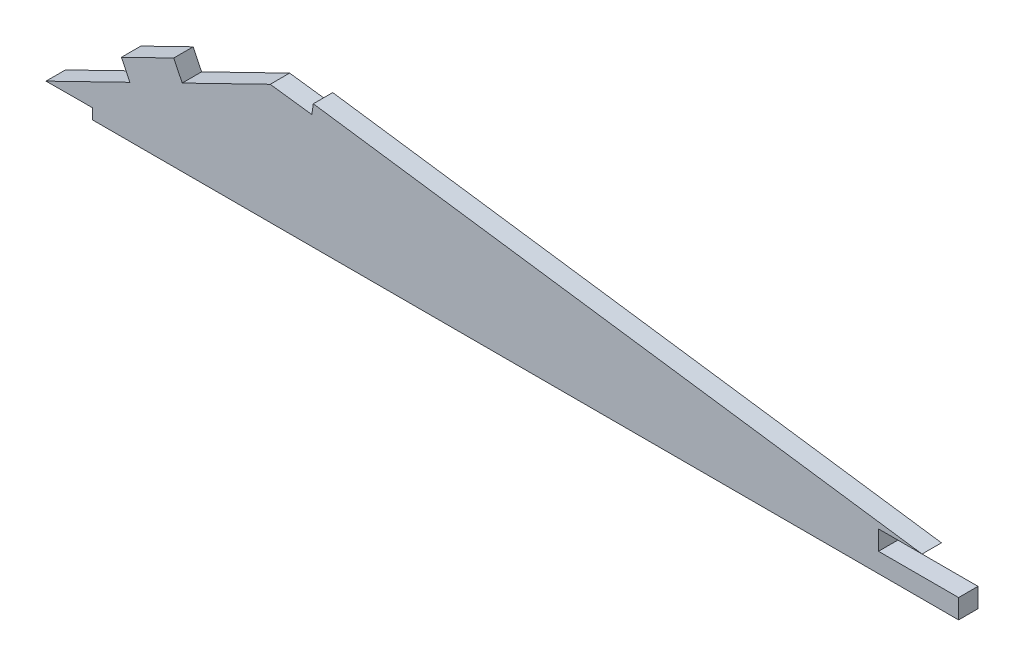
SolidWorks part; units mm, degrees
ref_plane "前视基准面" through (0, 0, 0) normal (0, 0, 1) x (1, 0, 0)
ref_plane "上视基准面" through (0, 0, 0) normal (0, 1, 0) x (1, 0, 0)
ref_plane "右视基准面" through (0, 0, 0) normal (1, 0, 0) x (0, 0, -1)
sketch "Model" plane through (0, 0, 0) normal (0, 0, 1) x (1, 0, 0)
  line L0 (10.8739, 9.301) -> (9.9972, 11.0986)
  line L1 (9.9972, 11.0986) -> (15.39, 13.7288)
  line L2 (15.39, 13.7288) -> (16.2667, 11.9312)
  line L3 (10.8739, 9.301) -> (2.2239, 5.0821)
  line L4 (16.2667, 11.9312) -> (25.3361, 16.3546)
  line L5 (7.0096, 4.0175) -> (96.2983, 4.0175)
  line L6 (7.0096, 4.0175) -> (7.0054, 5.1006)
  line L7 (7.0054, 5.1006) -> (2.2239, 5.0821)
  line L8 (88.0421, 6.0175) -> (96.2983, 6.0175)
  line L9 (88.0421, 8.0175) -> (92.5318, 8.0175)
  line L10 (88.0421, 6.0175) -> (88.0421, 8.0175)
  line L11 (96.2983, 4.0175) -> (96.2983, 6.0175)
  line L12 (29.7785, 16.8369) -> (92.5318, 8.0175)
  line L13 (25.3361, 16.3546) -> (29.6303, 15.7992)
  line L14 (29.6303, 15.7992) -> (29.7785, 16.8369)
  point P16 (29.7785, 16.8388)
extrude "凸台-拉伸1" add sketch "Model" along normal blind 2
